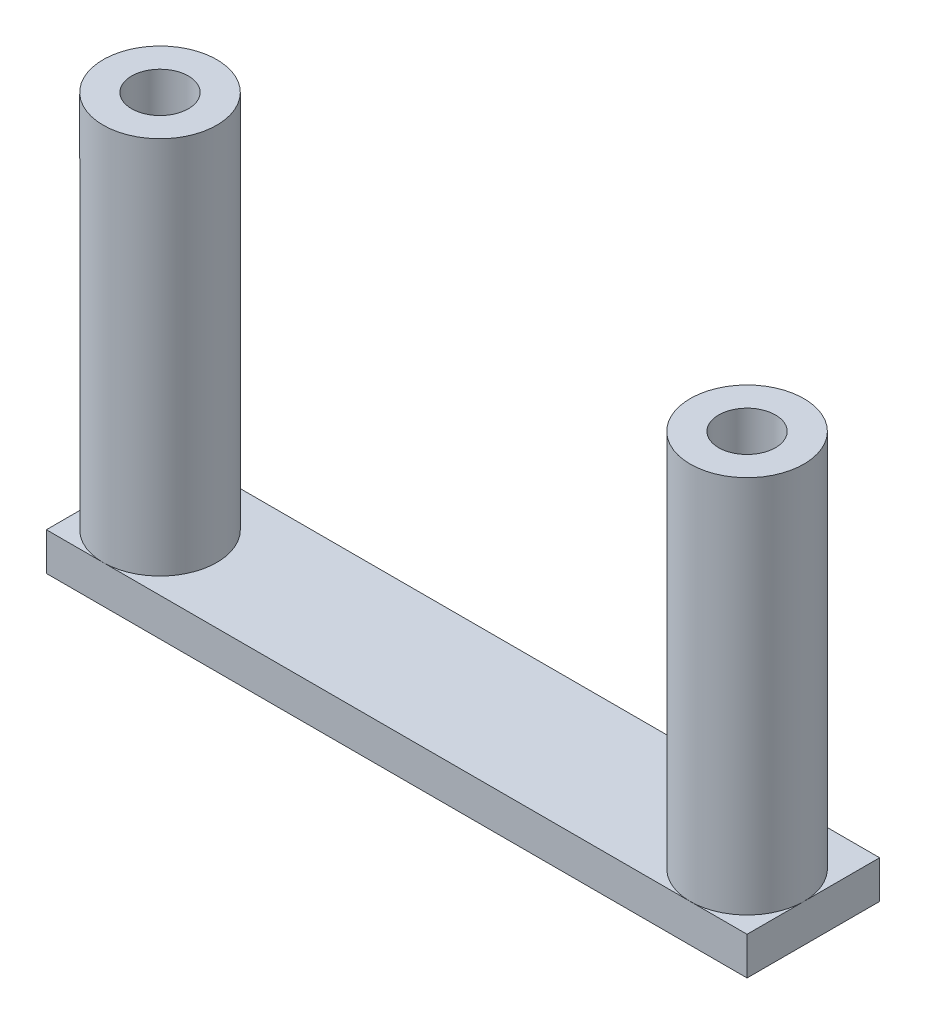
SolidWorks part; units mm, degrees
ref_plane "Front Plane" through (0, 0, 0) normal (0, 0, 1) x (1, 0, 0)
ref_plane "Top Plane" through (0, 0, 0) normal (0, 1, 0) x (1, 0, 0)
ref_plane "Right Plane" through (0, 0, 0) normal (1, 0, 0) x (0, 0, -1)
sketch "Sketch1" plane through (0, 0, 0) normal (0, 1, 0) x (1, 0, 0)
  line L0 (-3, 28) -> (34, 28)
  line L1 (0, 0) -> (31, 0)
  line L2 (0, 0) -> (0, 25)
  line L3 (0, 25) -> (31, 25)
  line L4 (31, 0) -> (31, 25)
  line L5 (34, -3) -> (34, 28)
  line L6 (-3, -3) -> (34, -3)
  line L7 (-3, -3) -> (-3, 28)
  circle A0 centre (0, 25) radius 1.5
  circle A1 centre (31, 25) radius 1.5
  circle A2 centre (31, 0) radius 1.5
  circle A3 centre (0, 0) radius 1.5
  dimension "D3" = 3
  dimension "D1" = 25
  dimension "D2" = 31
  dimension "D4" = 3
extrude "Boss-Extrude1" add sketch "Sketch1" along normal blind 2 contours L7 L6 L5 L0 A3 L2 A0 L3 A1 L4 A2 L1 | A3 L1 A2 L4 A1 L3 A0 L2
sketch "Sketch2" plane through (0, 2, 0) normal (0, 1, 0) x (1, 0, 0)
  circle A0 centre (31, 25) radius 1.5 construction
  circle A1 centre (31, 0) radius 1.5 construction
  circle A2 centre (0, 0) radius 1.5 construction
  circle A3 centre (0, 25) radius 1.5 construction
  circle A4 centre (31, 25) radius 1.5
  circle A5 centre (31, 0) radius 1.5
  circle A6 centre (0, 0) radius 1.5
  circle A7 centre (0, 25) radius 1.5
  circle A8 centre (0, 25) radius 3
  circle A9 centre (31, 25) radius 3
  circle A10 centre (31, 0) radius 3
  circle A11 centre (0, 0) radius 3
  dimension "D1" = 1.5
extrude "Boss-Extrude2" add sketch "Sketch2" along normal blind 20
sketch "Sketch3" plane through (0, 0, 0) normal (0, -1, 0) x (1, 0, 0)
  line L0 (-3, 3) -> (-3, -28) construction
  line L1 (34, -4) -> (-3, -4)
  line L2 (34, -4) -> (34, -28)
  line L3 (34, -28) -> (-3, -28)
  line L4 (-3, -4) -> (-3, -28)
  line L5 (-3, -28) -> (34, -28) construction
  line L6 (-3, 3) -> (34, 3) construction
  dimension "D1" = 0
  dimension "D2" = 0
  dimension "D3" = 7
extrude "Cut-Extrude1" cut sketch "Sketch3" against normal through all
